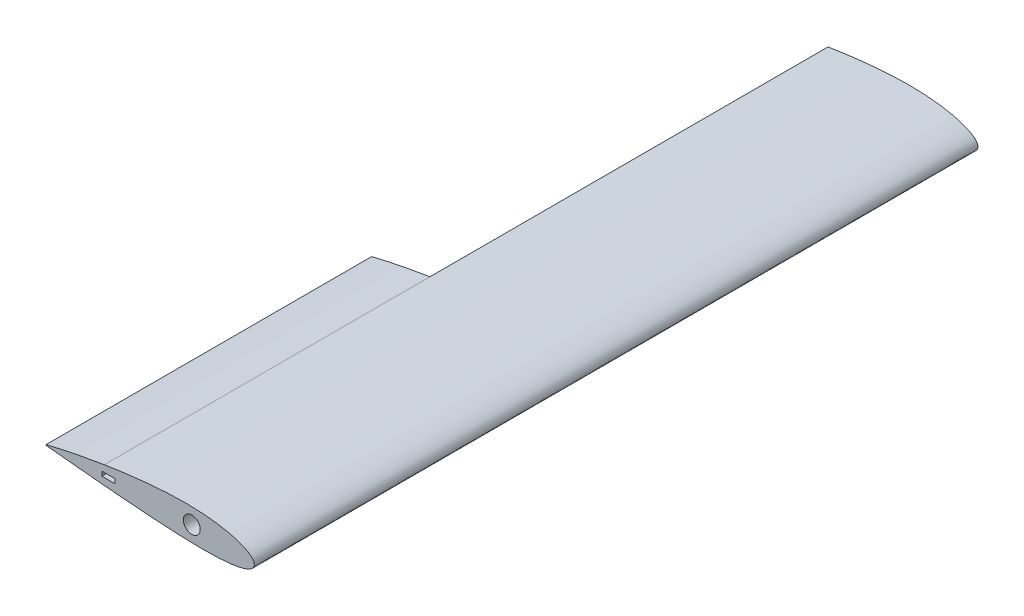
SolidWorks part; units mm, degrees
ref_plane "Front Plane" through (0, 0, 0) normal (0, 0, 1) x (1, 0, 0)
ref_plane "Top Plane" through (0, 0, 0) normal (0, 1, 0) x (1, 0, 0)
ref_plane "Right Plane" through (0, 0, 0) normal (1, 0, 0) x (0, 0, -1)
sketch "Sketch1" plane through (0, 0, 0) normal (0, 0, 1) x (1, 0, 0)
  line L0 (-232.0798, 18.6403) -> (-232.0798, -9.2995)
  spline S0 degree 3 poles (-232.0798, 18.6403) (-229.1643, 19.1051) (-222.2911, 20.2009) (-211.3375, 21.8003) (-199.1467, 23.4589) (-186.7095, 24.9978) (-174.1041, 26.3964) (-161.4086, 27.6282) (-148.7028, 28.67) (-136.0486, 29.4987) (-123.5023, 30.1004) (-111.1413, 30.381) (-99.0664, 30.3378) (-87.3818, 29.9639) (-76.166, 29.2625) (-65.4942, 28.2421) (-55.4376, 26.9176) (-46.0625, 25.3096) (-37.4298, 23.4441) (-29.5941, 21.3513) (-22.603, 19.0647) (-16.4967, 16.6189) (-11.3071, 14.0482) (-7.0567, 11.3833) (-3.7587, 8.6453) (-1.4211, 5.8377) (-0.0765, 2.934) (0.1754, -0.0176) (-0.6552, -2.8586) (-2.5307, -5.4396) (-5.3368, -7.7439) (-9.0399, -9.8146) (-13.6249, -11.6648) (-19.0703, -13.295) (-25.3465, -14.701) (-32.4168, -15.8791) (-40.2393, -16.8276) (-48.7681, -17.5483) (-57.9533, -18.0468) (-67.7426, -18.3331) (-78.0803, -18.4209) (-88.9087, -18.3281) (-100.1673, -18.0756) (-111.7935, -17.6875) (-123.7453, -17.1857) (-135.9735, -16.6041) (-148.4028, -15.8904) (-160.9356, -15.0745) (-173.4784, -14.1779) (-185.9552, -13.2219) (-198.2901, -12.2258) (-210.4075, -11.2062) (-221.6469, -10.2324) (-228.8379, -9.5894) (-232.0798, -9.2995) knots 0 0 0 0 0.018424 0.043434 0.06908 0.095203 0.12164 0.148227 0.1748 0.201195 0.227364 0.253182 0.278347 0.30271 0.326128 0.348467 0.3696 0.389416 0.407811 0.424699 0.440008 0.453688 0.465715 0.476104 0.484928 0.49236 0.49873 0.504587 0.510443 0.516804 0.524199 0.532941 0.543186 0.554996 0.568376 0.583299 0.599709 0.617539 0.636704 0.657109 0.678651 0.701217 0.724685 0.748928 0.773811 0.799338 0.825326 0.851504 0.877716 0.9038 0.929596 0.954944 0.979688 1 1 1 1
extrude "Boss-Extrude1" add sketch "Sketch1" against normal blind 1120
sketch "Sketch2" plane through (0, 0, 0) normal (0, 0, 1) x (1, 0, 0)
  line L0 (-232.0798, 18.6403) -> (-232.0798, -9.2995)
  line L1 (-322.333, 0.5148) -> (-322.333, -0.5066)
  spline S0 degree 3 poles (-232.0798, 18.6403) (-232.9971, 18.4966) (-237.5995, 17.7757) (-245.6979, 16.3987) (-256.1817, 14.5496) (-266.0705, 12.7084) (-275.3065, 10.9119) (-283.8343, 9.1839) (-291.6033, 7.5511) (-298.5679, 6.0388) (-304.6872, 4.6711) (-309.9259, 3.4706) (-314.2535, 2.4578) (-317.6452, 1.6505) (-320.0818, 1.0631) (-321.538, 0.709) (-322.1805, 0.552) (-322.333, 0.5148) knots 0 0 0 0 0.030252 0.151774 0.267626 0.37709 0.479485 0.574175 0.66057 0.73813 0.806369 0.864859 0.913229 0.951173 0.978451 0.994887 1 1 1 1
  spline S1 degree 3 poles (-232.0798, -9.2995) (-232.6657, -9.2475) (-236.9346, -8.868) (-244.7159, -8.1558) (-255.2335, -7.1827) (-265.179, -6.2448) (-274.4894, -5.353) (-283.1057, -4.5145) (-290.9725, -3.7372) (-298.0392, -3.0286) (-304.2602, -2.3953) (-309.5949, -1.8468) (-314.0082, -1.3828) (-317.4721, -1.0277) (-319.9612, -0.741) (-321.4641, -0.6201) (-322.142, -0.5059) (-322.3217, -0.5065) (-322.333, -0.5066) knots 0 0 0 0 0.019463 0.141781 0.258505 0.3689 0.472262 0.567931 0.655294 0.733785 0.802892 0.862162 0.911205 0.949694 0.977373 0.994054 0.999628 1 1 1 1
extrude "Boss-Extrude2" add sketch "Sketch2" against normal blind 504
sketch "Sketch3" plane through (0, 0, 0) normal (0, 0, 1) x (1, 0, 0)
  circle A0 centre (-96.7, 6.044) radius 13
extrude "Cut-Extrude1" cut sketch "Sketch3" against normal blind 801
ref_plane "Plane1" through (0, 0, -376.7) normal (0, 0, 1) x (1, 0, 0)
sketch "Sketch4" plane through (0, 0, -376.7) normal (0, 0, 1) x (1, 0, 0)
  line L0 (-112.7, -19.138) -> (-80.7, -19.138)
  line L1 (-80.7, -19.138) -> (-80.7, 21.744)
  line L2 (-80.7, 21.744) -> (-112.7, 21.744)
  line L3 (-112.7, 21.744) -> (-112.7, -19.138)
extrude "Cut-Extrude2" cut sketch "Sketch4" along normal blind 46
ref_plane "Plane2" through (0, 0, -376.7) normal (0, 0, 1) x (1, 0, 0)
sketch "Sketch5" plane through (0, 0, -376.7) normal (0, 0, 1) x (1, 0, 0)
  line L0 (-287.8664, -8.987) -> (-227.8664, -8.987)
  line L1 (-227.8664, -8.987) -> (-227.8664, 3.013)
  line L2 (-227.8664, 3.013) -> (-287.8664, 3.013)
  line L3 (-287.8664, 3.013) -> (-287.8664, -8.987)
extrude "Cut-Extrude3" cut sketch "Sketch5" along normal blind 46
ref_plane "Plane3" through (0, 0, -598.5) normal (0, 0, 1) x (1, 0, 0)
sketch "Sketch6" plane through (0, 0, -598.5) normal (0, 0, 1) x (1, 0, 0)
  line L0 (-204.283, -16.91) -> (-150.283, -16.91)
  line L1 (-150.283, -16.91) -> (-150.283, 12.19)
  line L2 (-150.283, 12.19) -> (-204.283, 12.19)
  line L3 (-204.283, 12.19) -> (-204.283, -16.91)
extrude "Cut-Extrude4" cut sketch "Sketch6" along normal blind 64
ref_plane "Plane4" through (0, 0, -25.5) normal (0, 0, 1) x (1, 0, 0)
sketch "Sketch7" plane through (0, 0, -25.5) normal (0, 0, 1) x (1, 0, 0)
  line L0 (-235.833, 1.435) -> (-215.433, 1.435)
  line L1 (-215.433, 1.435) -> (-215.433, 8.235)
  line L2 (-215.433, 8.235) -> (-235.833, 8.235)
  line L3 (-235.833, 8.235) -> (-235.833, 1.435)
extrude "Cut-Extrude5" cut sketch "Sketch7" along normal blind 26
ref_plane "Plane5" through (0, 0, -930) normal (0, 0, 1) x (1, 0, 0)
sketch "Sketch8" plane through (0, 0, -930) normal (0, 0, 1) x (1, 0, 0)
  line L0 (-60, -19.343) -> (-40, -19.343)
  line L1 (-40, -19.343) -> (-40, -15.343)
  line L2 (-40, -15.343) -> (-60, -15.343)
  line L3 (-60, -15.343) -> (-60, -19.343)
extrude "Cut-Extrude6" cut sketch "Sketch8" along normal blind 20
